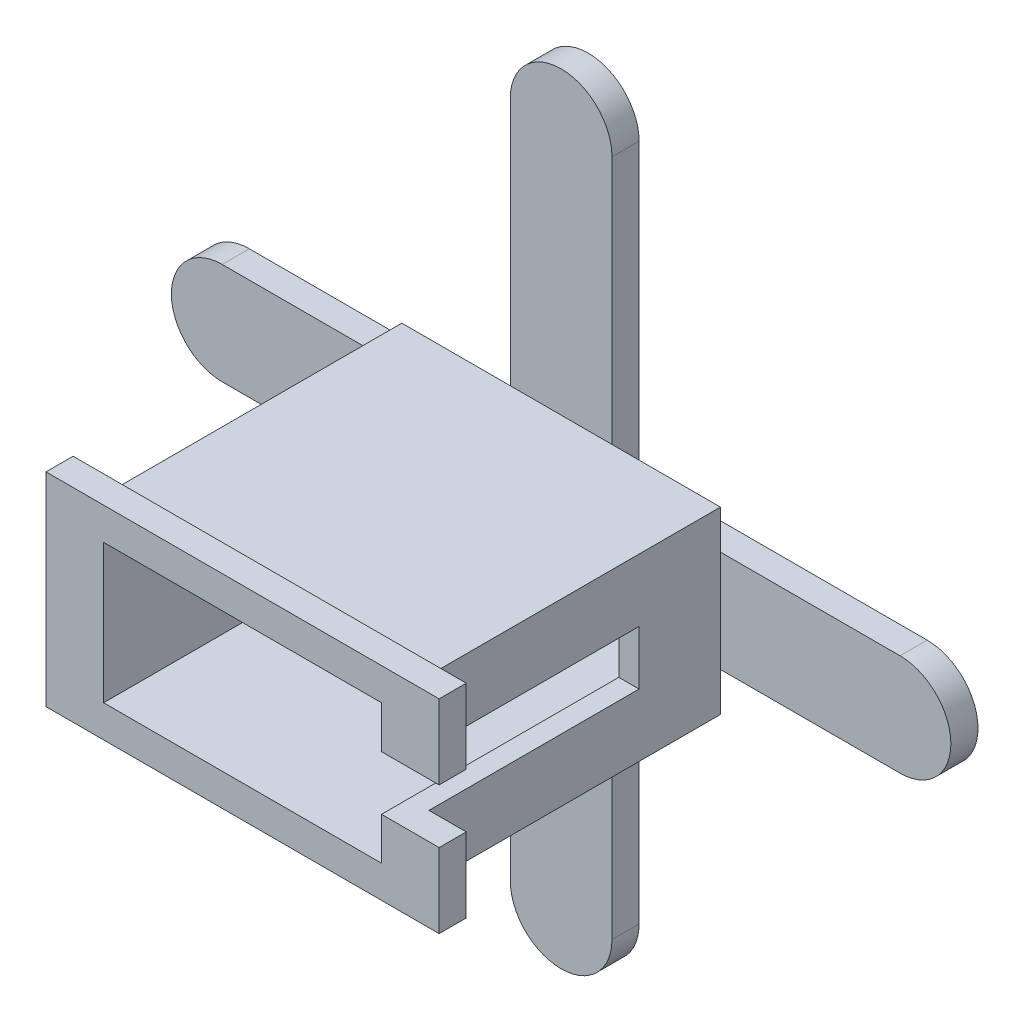
SolidWorks part; units mm, degrees
ref_plane "前视基准面" through (0, 0, 0) normal (0, 0, 1) x (1, 0, 0)
ref_plane "上视基准面" through (0, 0, 0) normal (0, 1, 0) x (1, 0, 0)
ref_plane "右视基准面" through (0, 0, 0) normal (1, 0, 0) x (0, 0, -1)
sketch "草图1" plane through (0, 0, 0) normal (0, 0, 1) x (1, 0, 0)
  line L0 (0, 0) -> (-9.5042, 0) construction
  line L2 (-7.5, 50) -> (-7.5, 7.5)
  line L4 (7.5, 50) -> (7.5, 7.5)
  line L5 (-7.5, 50) -> (-1.125, 7.5) construction
  line L6 (0, 0) -> (0, -6.1219) construction
  line L7 (-50, -7.5) -> (-7.5, -7.5)
  line L9 (-50, 7.5) -> (-7.5, 7.5)
  line L11 (0, 0) -> (7.5, 1.125) construction
  line L12 (7.5, -7.5) -> (50, -7.5)
  line L13 (1.125, -7.5) -> (7.5, -50) construction
  line L14 (7.5, -1.125) -> (50, -7.5) construction
  line L15 (-7.5, -7.5) -> (-7.5, -50)
  line L16 (0, 0) -> (7.5, 50) construction
  line L17 (7.5, -7.5) -> (7.5, -50)
  line L18 (7.5, 7.5) -> (50, 7.5)
  arc A0 (-7.5, 50) -> (7.5, 50) centre (0, 50) cw
  arc A1 (50, 7.5) -> (50, -7.5) centre (50, 0) cw
  arc A2 (-7.5, -50) -> (7.5, -50) centre (0, -50) ccw
  arc A3 (-50, 7.5) -> (-50, -7.5) centre (-50, 0) ccw
  point P0 (0, 0)
  point P5 (0, 0)
  dimension "D1" = 100
  dimension "D2" = 15
  dimension "D3" = 100
  dimension "D4" = 15
extrude "凸台-拉伸1" add sketch "草图1" along normal blind 4
sketch "草图2" plane through (0, 0, 4) normal (0, 0, 1) x (1, 0, 0)
  line L1 (-20.5, 10.25) -> (20.5, 10.25)
  line L2 (-20.5, 10.25) -> (-20.5, -10.25)
  line L3 (-20.5, -10.25) -> (20.5, -10.25)
  line L4 (20.5, 10.25) -> (20.5, -10.25)
  line L5 (-20.5, 10.25) -> (20.5, -10.25) construction
  line L6 (-20.5, -10.25) -> (20.5, 10.25) construction
  line L7 (-23.5, -13.25) -> (23.5, -13.25)
  line L8 (-23.5, -13.25) -> (-23.5, 13.25)
  line L9 (-23.5, 13.25) -> (23.5, 13.25)
  line L10 (23.5, -13.25) -> (23.5, 13.25)
  line L11 (-23.5, -13.25) -> (23.5, 13.25) construction
  line L12 (-23.5, 13.25) -> (23.5, -13.25) construction
  point P0 (0, 0)
  point P5 (0, 0)
  dimension "D1" = 20.5
  dimension "D2" = 41
  dimension "D3" = 3
  dimension "D4" = 3
extrude "凸台-拉伸2" add sketch "草图2" along normal blind 43
sketch "草图3" plane through (0, 0, 47) normal (0, 0, 1) x (1, 0, 0)
  line L0 (-20.5, -10.25) -> (20.5, -10.25) construction
  line L1 (20.5, -10.25) -> (20.5, 10.25) construction
  line L2 (20.5, 10.25) -> (-20.5, 10.25) construction
  line L3 (-20.5, 10.25) -> (-20.5, -10.25) construction
  line L4 (-20.5, -10.25) -> (20.5, -10.25)
  line L5 (20.5, -10.25) -> (20.5, 10.25)
  line L6 (20.5, 10.25) -> (-20.5, 10.25)
  line L7 (-20.5, 10.25) -> (-20.5, -10.25)
  line L9 (-29, -15) -> (29, -15)
  line L10 (-29, -15) -> (-29, 15)
  line L11 (-29, 15) -> (29, 15)
  line L12 (29, -15) -> (29, 15)
  line L13 (-29, -15) -> (29, 15) construction
  line L14 (-29, 15) -> (29, -15) construction
  point P2 (0, 0)
  dimension "D1" = 58
  dimension "D2" = 30
extrude "凸台-拉伸3" add sketch "草图3" along normal blind 4
sketch "草图4" plane through (0, 0, 51) normal (0, 0, 1) x (1, 0, 0)
  line L0 (0, 0) -> (75.2996, 0) construction
  line L2 (-4.4387, -4) -> (38.9973, -4)
  line L3 (-4.4387, -4) -> (-4.4387, 4)
  line L4 (-4.4387, 4) -> (38.9973, 4)
  line L5 (38.9973, -4) -> (38.9973, 4)
  line L6 (-4.4387, -4) -> (38.9973, 4) construction
  line L7 (-4.4387, 4) -> (38.9973, -4) construction
  point P3 (17.2793, 0)
  dimension "D1" = 8
extrude "切除-拉伸1" cut sketch "草图4" against normal blind 35
